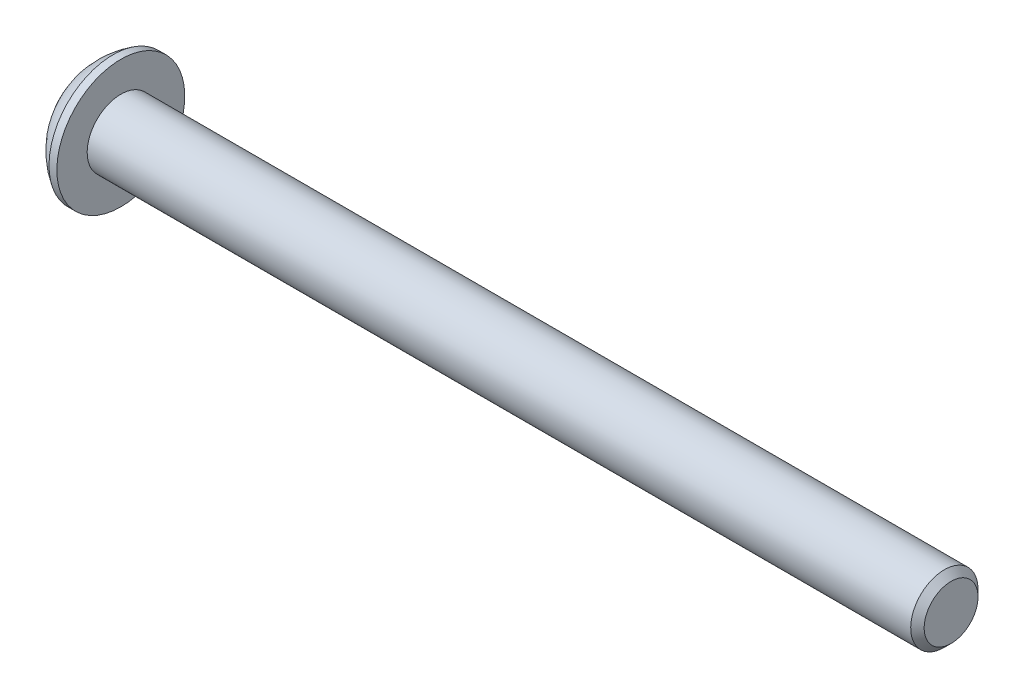
SolidWorks part; units mm, degrees
ref_plane "Front Plane" through (0, 0, 0) normal (0, 0, 1) x (1, 0, 0)
ref_plane "Top Plane" through (0, 0, 0) normal (0, 1, 0) x (1, 0, 0)
ref_plane "Right Plane" through (0, 0, 0) normal (1, 0, 0) x (0, 0, -1)
sketch "Sketch1" plane through (0, 0, 0) normal (0, 0, 1) x (1, 0, 0)
  line L0 (-45.1858, 0) -> (45.1858, 0) construction
  line L1 (-38.65, 0) -> (-38.65, 1.425)
  line L2 (-37.35, 2.85) -> (-37, 2.85)
  line L3 (-37, 2.85) -> (-37, 1.5)
  line L4 (-37, 1.5) -> (0, 1.5)
  line L5 (0, 1.5) -> (0, 0)
  line L6 (-38.65, 0) -> (0, 0)
  arc A0 (-38.65, 1.425) -> (-37.35, 2.85) centre (-35.6299, -0.0247) cw
  point P3 (0, 0)
  dimension "D3" = 1.65
  dimension "D5" = 2.85
  dimension "D6" = 3.35
  dimension "D1" = 37
  dimension "D2" = 0.35
  dimension "D4" = 1.425
  dimension "D7" = 1.5
revolve "Revolve1" add sketch "Sketch1" angle 360 about L0
sketch "Sketch2" plane through (-38.65, 0, 0) normal (-1, 0, 0) x (0, 0, 1)
  line L1 (0, 1.1547) -> (-1, 0.5774)
  line L2 (-1, 0.5774) -> (-1, -0.5774)
  line L3 (-1, -0.5774) -> (0, -1.1547)
  line L4 (0, -1.1547) -> (1, -0.5774)
  line L5 (1, -0.5774) -> (1, 0.5774)
  line L6 (1, 0.5774) -> (0, 1.1547)
  circle A0 centre (0, 0) radius 1 construction
  dimension "D1" = 2
extrude "Cut-Extrude1" cut sketch "Sketch2" against normal blind 1
chamfer "Chamfer1" distance 0.3 angle 45 1 edges at (0, -1.5, 0)
